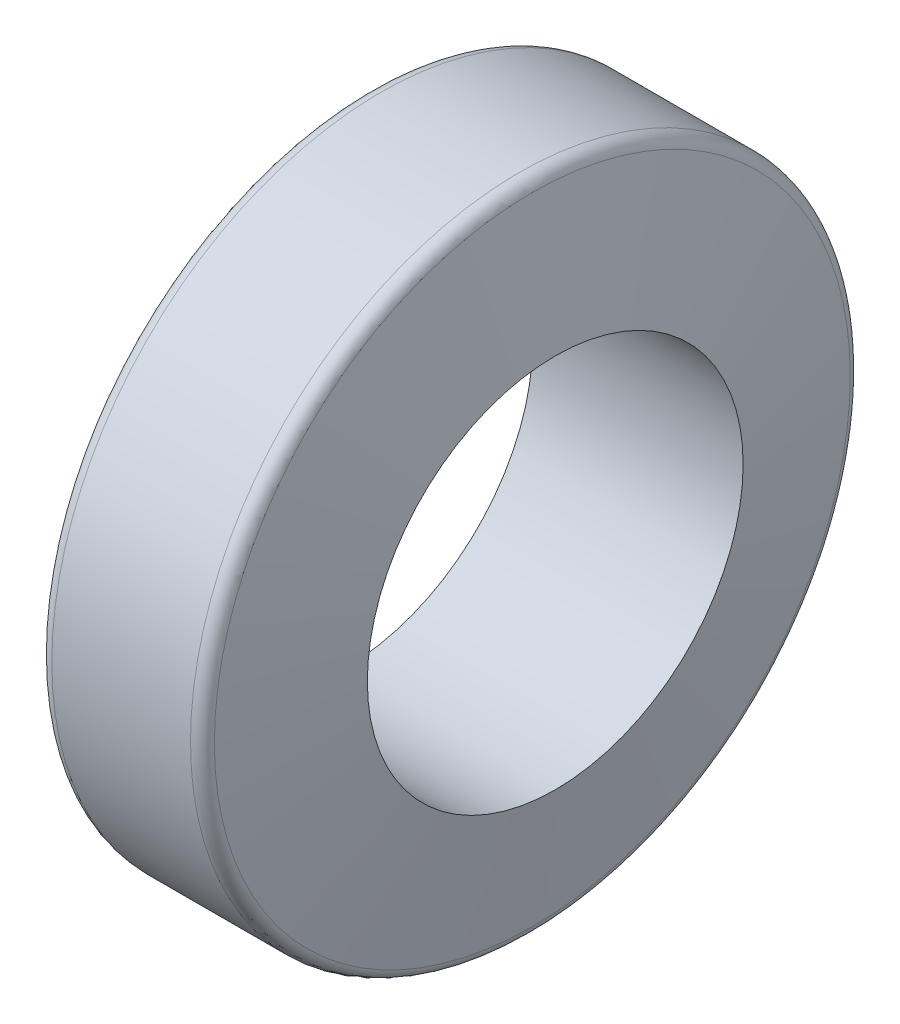
SolidWorks part; units mm, degrees
ref_plane "前视基准面" through (0, 0, 0) normal (0, 0, 1) x (1, 0, 0)
ref_plane "上视基准面" through (0, 0, 0) normal (0, 1, 0) x (1, 0, 0)
ref_plane "右视基准面" through (0, 0, 0) normal (1, 0, 0) x (0, 0, -1)
ref_plane "基准面4" through (0, 0, 0) normal (0, 0, 1) x (1, 0, 0)
sketch "草图1" plane through (0, 0, 0) normal (0, 0, 1) x (1, 0, 0)
  line L0 (-16, 28.5714) -> (16, 28.5714)
  line L1 (16, 28.5714) -> (12.513, 48.3473)
  line L2 (10.5434, 50) -> (-10.5434, 50)
  line L3 (-12.513, 48.3473) -> (-16, 28.5714)
  line L4 (50, 0) -> (-50, 0) construction
  arc A0 (12.513, 48.3473) -> (10.5434, 50) centre (10.5434, 48) ccw
  arc A1 (-10.5434, 50) -> (-12.513, 48.3473) centre (-10.5434, 48) ccw
revolve "旋转1" add sketch "草图1" angle 360 about L4
